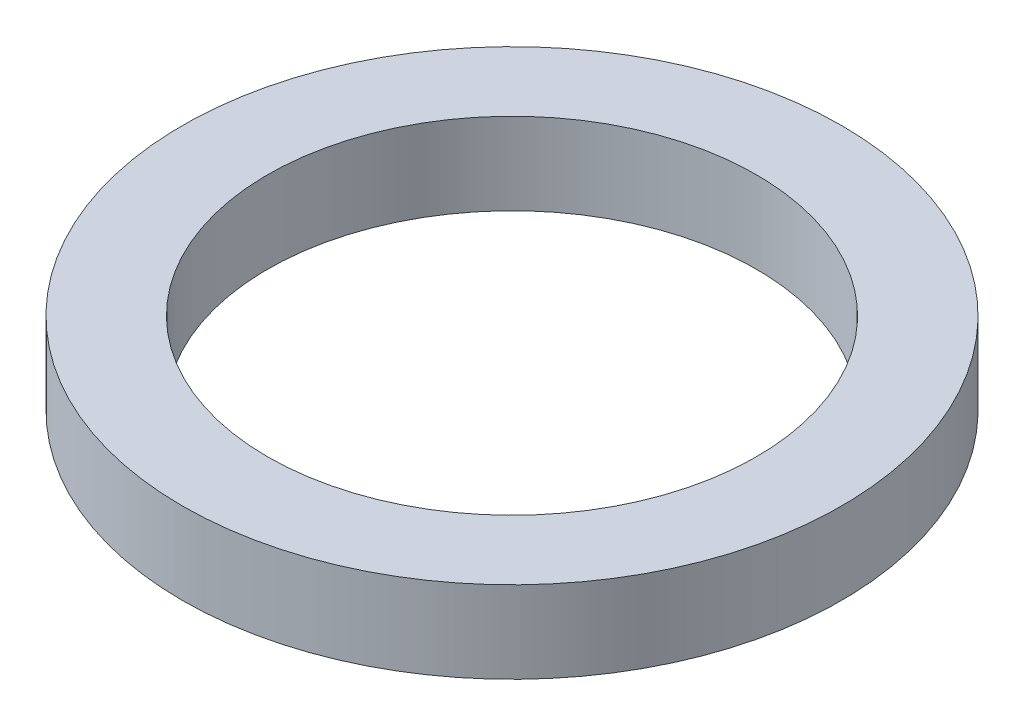
SolidWorks part; units mm, degrees
material "PET"
ref_plane "Front Plane" through (0, 0, 0) normal (0, 0, 1) x (1, 0, 0)
ref_plane "Top Plane" through (0, 0, 0) normal (0, 1, 0) x (1, 0, 0)
ref_plane "Right Plane" through (0, 0, 0) normal (1, 0, 0) x (0, 0, -1)
sketch "Sketch1" plane through (0, 0, 0) normal (0, 1, 0) x (1, 0, 0)
  circle A0 centre (0, 0) radius 80.5206
  circle A1 centre (0, 0) radius 59.7057
  dimension "D1" = 119.4114
extrude "body" add sketch "Sketch1" along normal blind 20
